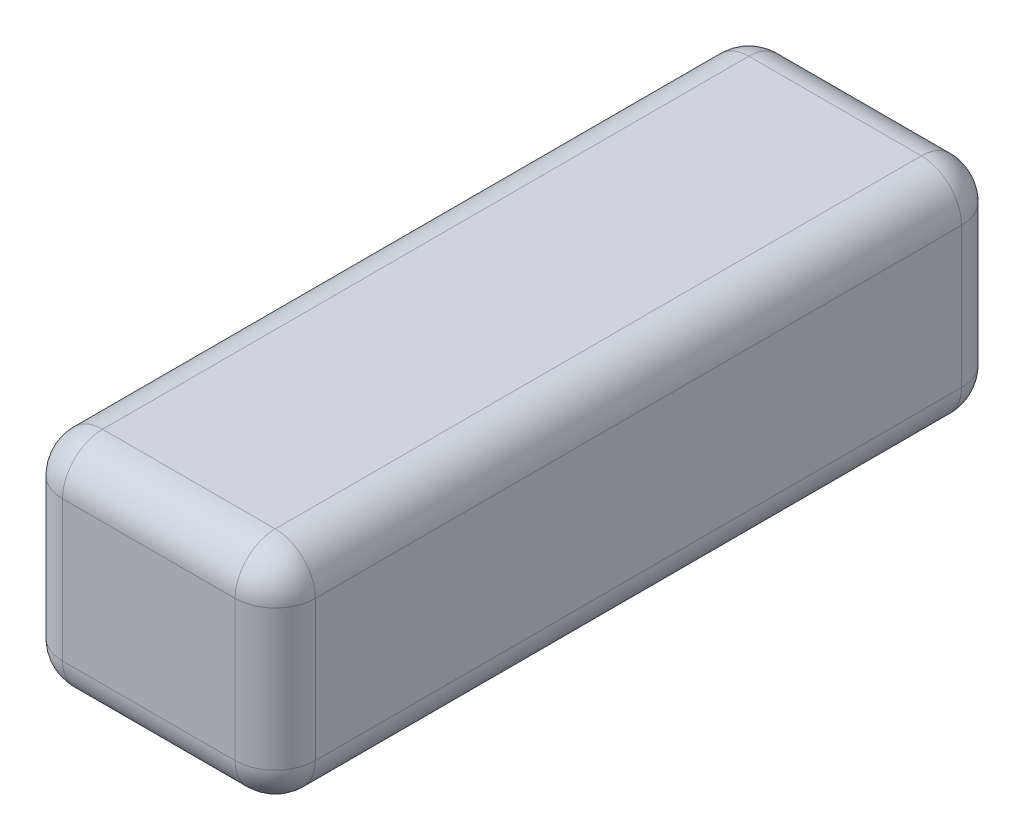
SolidWorks part; units mm, degrees
ref_plane "Front Plane" through (0, 0, 0) normal (0, 0, 1) x (1, 0, 0)
ref_plane "Top Plane" through (0, 0, 0) normal (0, 1, 0) x (1, 0, 0)
ref_plane "Right Plane" through (0, 0, 0) normal (1, 0, 0) x (0, 0, -1)
sketch "Sketch1" plane through (0, 0, 0) normal (0, 1, 0) x (1, 0, 0)
  line L1 (0, 0) -> (-16.002, 0)
  line L2 (0, 0) -> (0, 45.974)
  line L3 (0, 45.974) -> (-16.002, 45.974)
  line L4 (-16.002, 0) -> (-16.002, 45.974)
  dimension "D1" = 16.002
  dimension "D2" = 45.974
extrude "Boss-Extrude1" add sketch "Sketch1" along normal blind 13.97
fillet "Fillet1" radius 2.54 12 edges at (-16.002, 6.985, 0) (-8.001, 13.97, 0) (0, 6.985, 0) (-8.001, 0, 0) (-8.001, 0, -45.974) (-8.001, 13.97, -45.974) (0, 6.985, -45.974) (-16.002, 6.985, -45.974) (-16.002, 0, -22.987) (-16.002, 13.97, -22.987) (0, 0, -22.987) (0, 13.97, -22.987)
